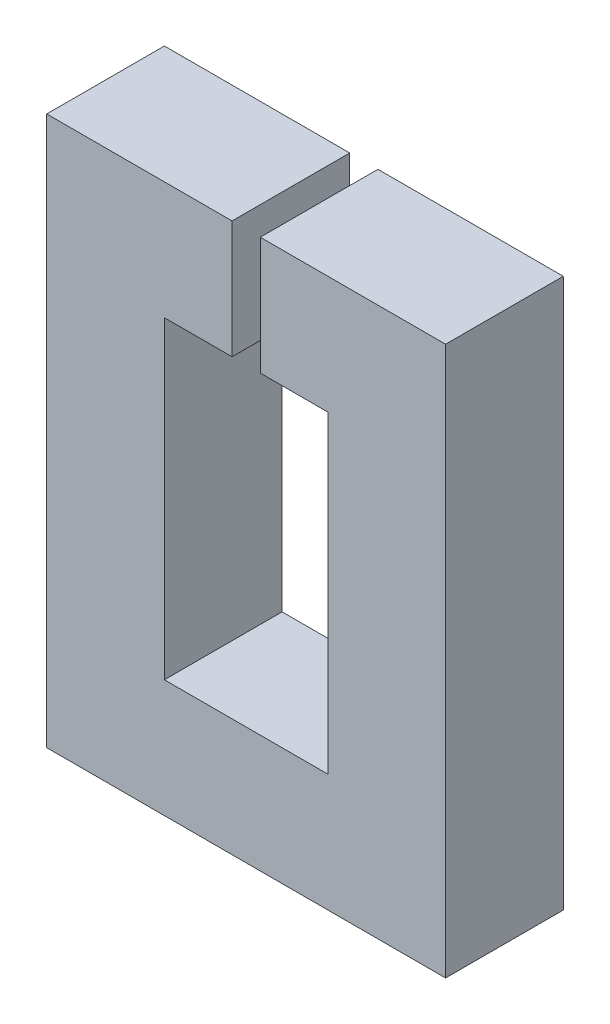
SolidWorks part; units mm, degrees
ref_plane "Ebene vorne" through (0, 0, 0) normal (0, 0, 1) x (1, 0, 0)
ref_plane "Ebene oben" through (0, 0, 0) normal (0, 1, 0) x (1, 0, 0)
ref_plane "Ebene rechts" through (0, 0, 0) normal (1, 0, 0) x (0, 0, -1)
sketch "Skizze1" plane through (0, 0, 0) normal (0, 0, 1) x (1, 0, 0)
  line L0 (-20.85, 39.975) -> (-20.85, -39.975)
  line L1 (-50.85, 69.975) -> (-3.6, 69.975)
  line L2 (-50.85, 69.975) -> (-50.85, -69.975)
  line L3 (-50.85, -69.975) -> (50.85, -69.975)
  line L4 (50.85, 69.975) -> (50.85, -69.975)
  line L5 (-50.85, 69.975) -> (50.85, -69.975) construction
  line L6 (-50.85, -69.975) -> (50.85, 69.975) construction
  line L7 (-20.85, -39.975) -> (20.85, -39.975)
  line L8 (20.85, 39.975) -> (20.85, -39.975)
  line L9 (-20.85, 39.975) -> (-3.6, 39.975)
  line L12 (0, 69.975) -> (0, -69.975) construction
  line L13 (-3.6, 69.975) -> (-3.6, 39.975)
  line L14 (3.6, 69.975) -> (3.6, 39.975)
  line L15 (3.6, 69.975) -> (50.85, 69.975)
  line L16 (3.6, 39.975) -> (20.85, 39.975)
  line L17 (-50.85, 69.975) -> (50.85, 69.975) construction
  line L19 (-20.85, 39.975) -> (20.85, 39.975) construction
  point P0 (0, 0)
  dimension "D1" = 101.7
  dimension "D3" = 139.95
  dimension "D4" = 7.2
  dimension "D2" = 30
extrude "Aufsatz-Linear austragen1" add sketch "Skizze1" along normal blind 30
